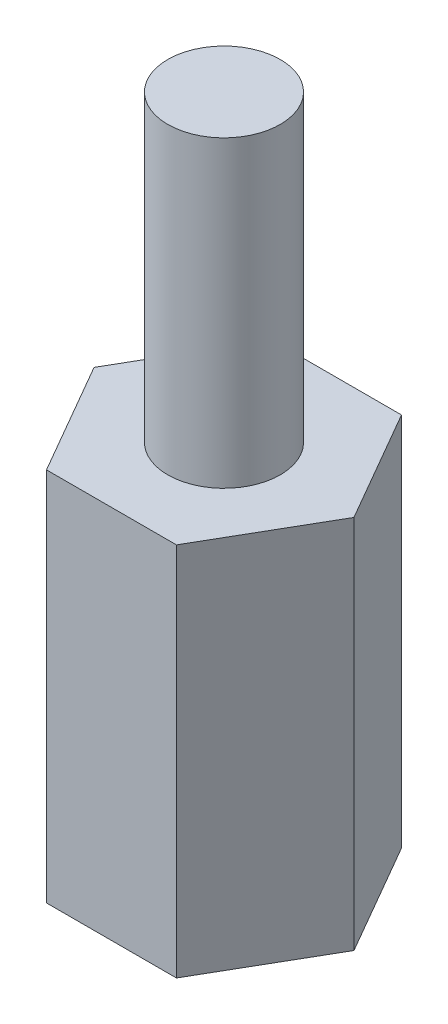
SolidWorks part; units mm, degrees
ref_plane "Front Plane" through (0, 0, 0) normal (0, 0, 1) x (1, 0, 0)
ref_plane "Top Plane" through (0, 0, 0) normal (0, 1, 0) x (1, 0, 0)
ref_plane "Right Plane" through (0, 0, 0) normal (1, 0, 0) x (0, 0, -1)
sketch "Sketch3" plane through (0, 0, 0) normal (0, 1, 0) x (1, 0, 0)
  line L1 (-3.4641, 0) -> (-1.7321, -3)
  line L2 (-1.7321, -3) -> (1.7321, -3)
  line L3 (1.7321, -3) -> (3.4641, 0)
  line L4 (3.4641, 0) -> (1.7321, 3)
  line L5 (1.7321, 3) -> (-1.7321, 3)
  line L6 (-1.7321, 3) -> (-3.4641, 0)
  circle A0 centre (0, 0) radius 3 construction
  dimension "D1" = 6
extrude "Boss-Extrude1" add sketch "Sketch3" along normal blind 10
sketch "Sketch5" plane through (0, 10, 0) normal (0, 1, 0) x (1, 0, 0)
  circle A0 centre (0, 0) radius 1.5
  dimension "D1" = 3
extrude "Boss-Extrude2" add sketch "Sketch5" along normal blind 8.0916
sketch "Sketch6" plane through (0, 0, 0) normal (0, -1, 0) x (1, 0, 0)
  circle A0 centre (0, 0) radius 1.5
extrude "Cut-Extrude1" cut sketch "Sketch6" against normal blind 4
